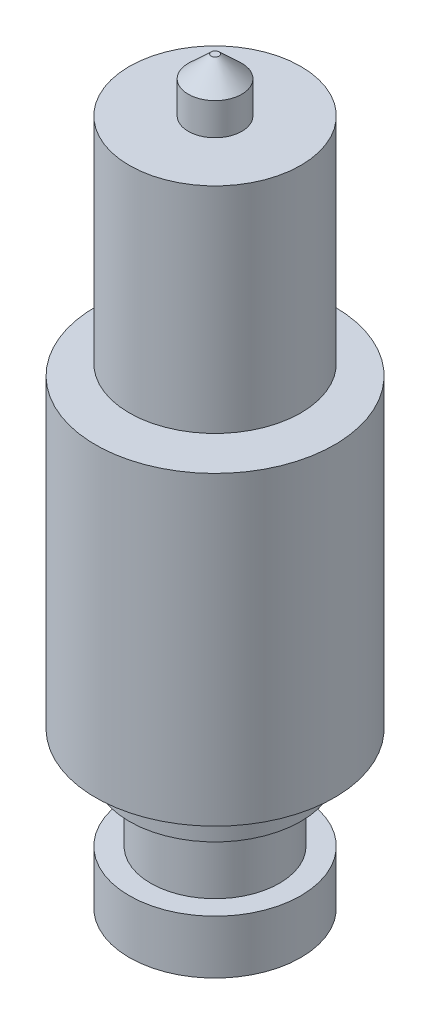
SolidWorks part; units mm, degrees
material "AISI 1035 Steel (SS)"
ref_plane "Front Plane" through (0, 0, 0) normal (0, 0, 1) x (1, 0, 0)
ref_plane "Top Plane" through (0, 0, 0) normal (0, 1, 0) x (1, 0, 0)
ref_plane "Right Plane" through (0, 0, 0) normal (1, 0, 0) x (0, 0, -1)
sketch "Sketch1" plane through (0, 0, 0) normal (0, 1, 0) x (1, 0, 0)
  circle A0 centre (0, 0) radius 8
  dimension "D1" = 16
extrude "Boss-Extrude1" add sketch "Sketch1" along normal blind 5
sketch "Sketch2" plane through (0, 5, 0) normal (0, 1, 0) x (1, 0, 0)
  circle A0 centre (0, 0) radius 6
  dimension "D1" = 12
extrude "Boss-Extrude2" add sketch "Sketch2" along normal blind 6
sketch "Sketch3" plane through (0, 11, 0) normal (0, 1, 0) x (1, 0, 0)
  circle A0 centre (0, 0) radius 8
  dimension "D1" = 16
extrude "Boss-Extrude3" add sketch "Sketch3" along normal blind 1.5
sketch "Sketch4" plane through (0, 12.5, 0) normal (0, 1, 0) x (1, 0, 0)
  circle A0 centre (0, 0) radius 5
  dimension "D1" = 10
extrude "Boss-Extrude4" add sketch "Sketch4" along normal blind 2
sketch "Sketch5" plane through (0, 14.5, 0) normal (0, 1, 0) x (1, 0, 0)
  circle A0 centre (0, 0) radius 11.15
  dimension "D1" = 22.3
extrude "Boss-Extrude5" add sketch "Sketch5" along normal blind 28.5
sketch "Sketch6" plane through (0, 43, 0) normal (0, 1, 0) x (1, 0, 0)
  circle A0 centre (0, 0) radius 2
  dimension "D1" = 4
extrude "Boss-Extrude6" add sketch "Sketch6" along normal blind 1
sketch "Sketch7" plane through (0, 44, 0) normal (0, 1, 0) x (1, 0, 0)
  circle A0 centre (0, 0) radius 8
  dimension "D1" = 16
extrude "Boss-Extrude7" add sketch "Sketch7" along normal blind 20
sketch "Sketch8" plane through (0, 64, 0) normal (0, 1, 0) x (1, 0, 0)
  circle A0 centre (0, 0) radius 2.5
  dimension "D1" = 5
extrude "Boss-Extrude8" add sketch "Sketch8" along normal blind 3
sketch "Sketch9" plane through (0, 67, 0) normal (0, 1, 0) x (1, 0, 0)
  circle A0 centre (0, 0) radius 2.5
extrude "Boss-Extrude9" add sketch "Sketch9" along normal blind 2 draft 47
ref_plane "Plane1" through (0, 0, 0) normal (0, 0, 1) x (1, 0, 0)
equation "\"D1@Boss-Extrude5\"=43-12.5-2"
